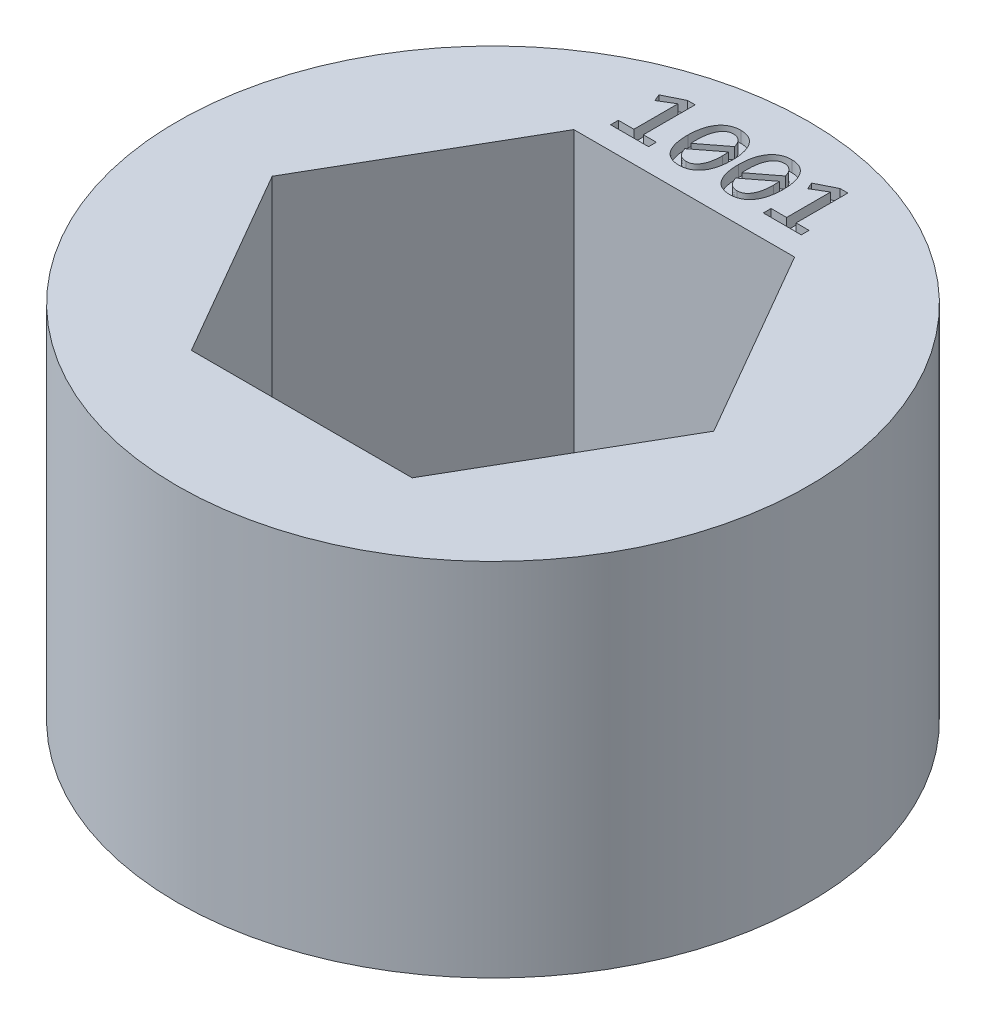
SolidWorks part; units mm, degrees
material "Nylon 101"
ref_plane "Front Plane" through (0, 0, 0) normal (0, 0, 1) x (1, 0, 0)
ref_plane "Top Plane" through (0, 0, 0) normal (0, 1, 0) x (1, 0, 0)
ref_plane "Right Plane" through (0, 0, 0) normal (1, 0, 0) x (0, 0, -1)
sketch "Sketch1" plane through (0, 0, 0) normal (0, 1, 0) x (1, 0, 0)
  line L1 (7.7723, 0) -> (3.8861, 6.731)
  line L2 (3.8861, 6.731) -> (-3.8861, 6.731)
  line L3 (-3.8861, 6.731) -> (-7.7723, 0)
  line L4 (-7.7723, 0) -> (-3.8861, -6.731)
  line L5 (-3.8861, -6.731) -> (3.8861, -6.731)
  line L6 (3.8861, -6.731) -> (7.7723, 0)
  circle A0 centre (0, 0) radius 6.731 construction
  circle A1 centre (0, 0) radius 11.1125
  dimension "D1" = 13.462
  dimension "D2" = 22.225
extrude "Boss-Extrude1" add sketch "Sketch1" along normal blind 12.7
sketch "Sketch2" plane through (0, 12.7, 0) normal (0, 1, 0) x (1, 0, 0)
  line L0 (-4.2615, 7.5247) -> (4.1119, 7.5247) construction
  line L1 (3.8861, 6.731) -> (-3.8861, 6.731) construction
  text T0 "1001" font "Consolas" height in points 8
  dimension "D1" = 0.7937
extrude "Cut-Extrude1" cut sketch "Sketch2" against normal blind 0.4
